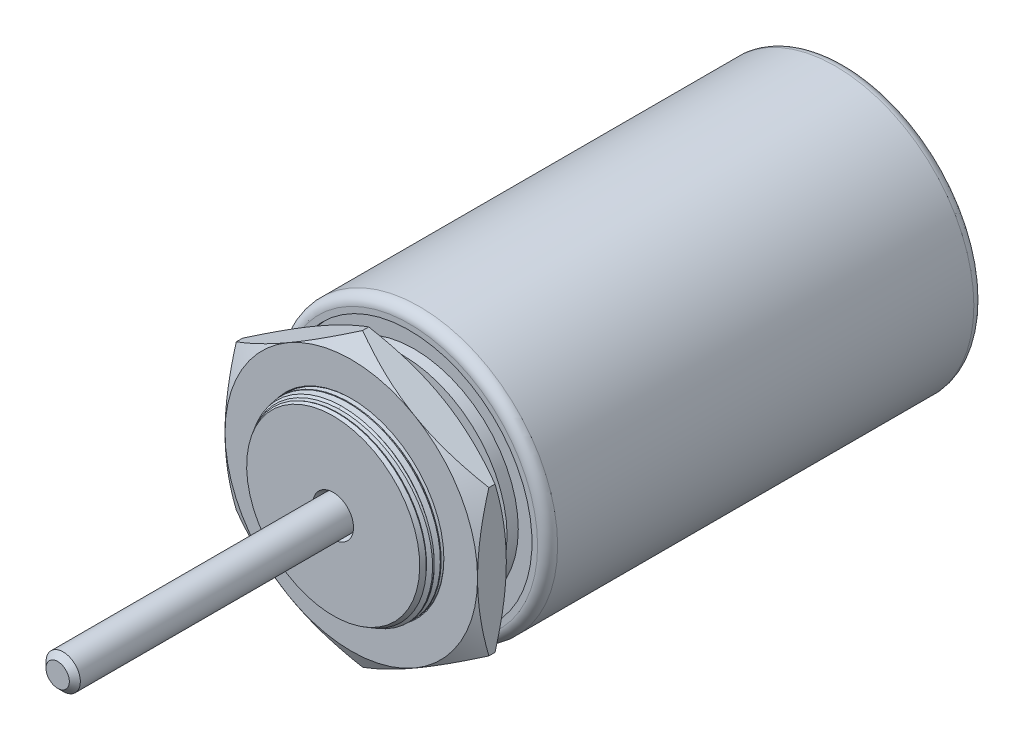
SolidWorks part; units mm, degrees
ref_plane "Front Plane" through (0, 0, 0) normal (0, 0, 1) x (1, 0, 0)
ref_plane "Top Plane" through (0, 0, 0) normal (0, 1, 0) x (1, 0, 0)
ref_plane "Right Plane" through (0, 0, 0) normal (1, 0, 0) x (0, 0, -1)
sketch "Sketch0" plane through (0, 0, 0) normal (1, 0, 0) x (0, 0, -1)
  line L0 (0, 0) -> (61.214, 0) construction
  line L1 (0, 0) -> (-26.3144, 0) construction
  line L2 (61.214, 19.1135) -> (61.214, -19.1135) construction
  line L3 (0, 12.7) -> (0, -12.7) construction
  line L4 (-26.3144, 2.3749) -> (-26.3144, -2.3749) construction
  line L5 (-26.3144, 0) -> (-51.7144, 0) construction
  line L6 (61.214, 0) -> (86.614, 0) construction
  line L7 (86.614, 0) -> (91.6432, 0) construction
  line L8 (88.4682, 6.35) -> (88.4682, -6.35) construction
  line L9 (91.6432, 2.8575) -> (91.6432, -2.8575) construction
  point P12 (-9.652, 0)
  point P17 (88.4682, 0)
  dimension "D1" = 5.715
  dimension "Lg." = 61.214
  dimension "Dia." = 38.227
  dimension "Rod Dia." = 4.7498
  dimension "A" = 42.0624
  dimension "Thread OD" = 25.4
  dimension "Stroke" = 25.4
  dimension "D2" = 3.175
  dimension "D3" = 9.652
  dimension "D4" = 5.0292
  dimension "End Dia." = 12.7
  dimension "D5" = 26.3144
sketch "Sketch1" plane through (0, 0, 0) normal (1, 0, 0) x (0, 0, -1)
  line L0 (61.214, 0) -> (0, 0) construction
  line L1 (59.8297, 19.1135) -> (2.2733, 19.1135)
  line L2 (0, 6.35) -> (61.214, 6.35)
  line L4 (1.5494, 16.9507) -> (1.5494, 14.3967)
  line L5 (61.214, 6.35) -> (61.214, 17.7292)
  line L6 (0.889, 17.7292) -> (0.889, 16.9507)
  line L7 (0.889, 16.9507) -> (1.5494, 16.9507)
  line L8 (1.5494, 14.3967) -> (0, 14.3967)
  line L9 (0, 14.3967) -> (0, 6.35)
  arc A1 (61.214, 17.7292) -> (59.8297, 19.1135) centre (59.8297, 17.7292) ccw
  arc A2 (0.889, 17.7292) -> (2.2733, 19.1135) centre (2.2733, 17.7292) cw
  dimension "D1" = 1.3843
  dimension "D4" = 0.889
  dimension "D5" = 33.9014
  dimension "D6" = 0.6604
  dimension "D7" = 28.7934
revolve "Revolve1" add sketch "Sketch1" angle 360 mid plane about L0
sketch "Sketch2" plane through (0, 0, 0) normal (1, 0, 0) x (0, 0, -1)
  line L0 (0, 0) -> (-26.3144, 0) construction
  line L3 (-9.652, 2.8148) -> (-9.652, 11.9668)
  line L4 (-9.652, 11.9668) -> (-8.382, 12.7)
  line L5 (-8.382, 12.7) -> (-3.2639, 12.7)
  line L6 (-3.2639, 12.7) -> (-1.5494, 10.9855)
  line L7 (-1.5494, 10.9855) -> (0, 10.9855)
  line L8 (0, 10.9855) -> (0, 2.3749)
  line L9 (-8.89, 2.3749) -> (0, 2.3749)
  line L11 (-8.89, 2.3749) -> (-9.652, 2.8148)
  dimension "D1" = 1.5494
  dimension "D2" = 45
  dimension "D3" = 30
  dimension "D4" = 1.27
  dimension "D5" = 9.652
  dimension "D6" = 1.7145
  dimension "D7" = 30
  dimension "D8" = 0.762
revolve "Revolve2" add sketch "Sketch2" angle 360 mid plane about L0
sketch "Sketch3" plane through (0, 0, 0) normal (1, 0, 0) x (0, 0, -1)
  line L0 (-9.652, 11.9668) -> (-9.652, -11.9668) construction
  line L1 (-46.99, 2.3749) -> (-47.752, 1.6129)
  line L2 (70.2056, 0) -> (-47.752, 0)
  line L3 (3.9624, 2.3749) -> (-46.99, 2.3749)
  line L4 (-47.752, 0) -> (-47.752, 1.6129)
  line L5 (-46.99, 2.3749) -> (-47.752, 2.3749) construction
  line L6 (-47.752, 2.3749) -> (-47.752, 1.6129) construction
  line L7 (3.9624, 6.35) -> (67.0306, 6.35)
  line L8 (67.0306, 6.35) -> (67.0306, 2.8575)
  line L9 (70.2056, 2.8575) -> (70.2056, 0)
  line L10 (67.0306, 2.8575) -> (70.2056, 2.8575)
  line L11 (3.9624, 6.35) -> (3.9624, 2.3749)
  point P1 (-59.6085, 69.5077)
  point P2 (-49.0748, 67.6511)
  point P3 (-63.5711, 53.1469)
  point P4 (-26.3144, 0)
  point P5 (-26.3144, 0)
  point P12 (-26.3144, 0)
  point P18 (0, 0)
  dimension "D1" = 0.762
  dimension "D2" = 2.3749
  dimension "D3" = 117.9576
  dimension "D4" = 63.0682
  dimension "D5" = 50.9524
  dimension "D6" = 3.9751
  dimension "D7" = 3.4925
  dimension "D8" = 38.1
revolve "Revolve3" add sketch "Sketch3" angle 360 mid plane about L2
sketch "Sketch6" plane through (0, 0, 9.652) normal (0, 0, 1) x (1, 0, 0)
  circle A1 centre (0, 0) radius 12.7
  point P1 (0, 12.7)
curve "Helix/Spiral1" pitch 0.9407 height 9.0433 turns 9.613 parameters "Pitch"=0.9407
sketch "Sketch7" plane through (0, 0, 0) normal (1, 0, 0) x (0, 0, -1)
  line L0 (-10.5339, 12.8018) -> (-9.5932, 12.8018) construction
  line L1 (-9.5932, 12.8018) -> (-10.0636, 11.9871) construction
  line L2 (-10.0636, 11.9871) -> (-10.5339, 12.8018) construction
  line L3 (-10.1224, 12.089) -> (-10.0048, 12.089) construction
  line L4 (-10.4751, 12.7) -> (-9.652, 12.7) construction
  line L5 (-10.0636, 11.9871) -> (-10.0636, 12.089) construction
  line L6 (-10.0636, 12.7) -> (-10.0636, 12.8018) construction
  line L7 (-10.1224, 12.089) -> (-10.0048, 12.089)
  line L8 (-10.0048, 12.089) -> (-9.6226, 12.7509)
  line L9 (-9.6226, 12.7509) -> (-10.5045, 12.7509)
  line L10 (-10.5045, 12.7509) -> (-10.1224, 12.089)
  line L11 (-10.0636, 11.9871) -> (-10.0636, -12.7) construction
  line L12 (-10.0636, -12.7) -> (-9.1228, -12.7) construction
  line L13 (-9.1228, -12.7) -> (-8.1821, -12.7) construction
  line L14 (-8.1821, -12.7) -> (-7.2414, -12.7) construction
  line L15 (-8.382, -12.7) -> (-3.2639, -12.7) construction
  point P15 (-10.0636, 12.7509)
  dimension "D1" = 0.9407
  dimension "D2" = 0.1176
sweep "Cut-Sweep1" cut profiles "Sketch7" path "Helix/Spiral1"
move or copy body "Body-Move/Copy1" [suppressed] bodies to move or copy 105 copy yes number of copies 1 translate (0, 0, 25.4)
sketch "SketchX" [suppressed] plane through (0, 0, 0) normal (1, 0, 0) x (0, 0, -1)
  line L3 (-51.7144, 1.6129) -> (-51.7144, -1.6129) construction
  line L4 (-51.7144, 1.6129) -> (-51.7144, -1.6129)
  line L6 (-50.9524, 2.3749) -> (-51.7144, 1.6129) construction
  line L9 (0, 2.3749) -> (-50.9524, 2.3749) construction
  line L10 (-51.7144, -1.6129) -> (-50.9524, -2.3749) construction
  line L13 (-50.9524, -2.3749) -> (0, -2.3749) construction
  line L14 (-50.9524, 2.3749) -> (-51.7144, 1.6129)
  line L15 (-25.5524, 2.3749) -> (-50.9524, 2.3749)
  line L16 (-51.7144, -1.6129) -> (-50.9524, -2.3749)
  line L17 (-50.9524, -2.3749) -> (-25.5524, -2.3749)
  line L18 (63.0682, 6.35) -> (0, 6.35) construction
  line L19 (63.0682, -6.35) -> (63.0682, 6.35) construction
  line L20 (66.2432, 2.8575) -> (63.0682, 2.8575) construction
  line L21 (66.2432, -2.8575) -> (66.2432, 2.8575) construction
  line L22 (0, -6.35) -> (63.0682, -6.35) construction
  line L23 (63.0682, 6.35) -> (61.214, 6.35)
  line L24 (63.0682, -6.35) -> (63.0682, -2.8575)
  line L25 (66.2432, 2.8575) -> (63.0682, 2.8575)
  line L26 (66.2432, -2.8575) -> (66.2432, 2.8575)
  line L27 (61.214, -6.35) -> (63.0682, -6.35)
  line L28 (61.214, -17.7292) -> (61.214, 17.7292) construction
  line L29 (63.0682, -2.8575) -> (66.2432, -2.8575) construction
  line L30 (63.0682, -2.8575) -> (66.2432, -2.8575)
  line L31 (63.0682, 2.8575) -> (63.0682, 6.35)
delete or keep bodies "Body-Delete1" [suppressed] type delete bodies bodies 108
sketch "Sketch8" plane through (0, 0, -61.214) normal (0, 0, -1) x (-1, 0, 0)
  line L0 (-15.9512, -2.54) -> (-15.9512, 2.54) construction
  line L1 (0, 0) -> (-15.9512, 0) construction
  circle A0 centre (-15.9512, 2.54) radius 0.254
  circle A1 centre (-15.9512, -2.54) radius 0.254
  dimension "D1" = 0.508
  dimension "D2" = 5.08
  dimension "D3" = 15.9512
extrude "Boss-Extrude1" [suppressed] add sketch "Sketch8" along normal blind 165.1
sketch "Sketch9" plane through (0, 0, -61.214) normal (0, 0, -1) x (-1, 0, 0)
  circle A0 centre (-15.9512, 2.54) radius 0.762
  circle A1 centre (-15.9512, -2.54) radius 0.762
  circle A3 centre (-15.9512, -2.54) radius 0.254
  circle A4 centre (-15.9512, -2.54) radius 0.254
  circle A5 centre (-15.9512, 2.54) radius 0.254
  circle A6 centre (-15.9512, 2.54) radius 0.254
  dimension "D3" = 1.524
  dimension "D1" = 0
  dimension "D2" = 0
extrude "Boss-Extrude2" [suppressed] add sketch "Sketch9" along normal blind 152.4
sketch "Sketch10" plane through (0, 0, 0) normal (0, 0, 1) x (1, 0, 0)
  line L0 (0, 12.7) -> (0, 17.4625) construction
  line L1 (0, 20.164) -> (-17.4625, 10.082)
  line L2 (-17.4625, 10.082) -> (-17.4625, -10.082)
  line L3 (-17.4625, -10.082) -> (0, -20.164)
  line L4 (0, -20.164) -> (17.4625, -10.082)
  line L5 (17.4625, -10.082) -> (17.4625, 10.082)
  line L6 (17.4625, 10.082) -> (0, 20.164)
  circle A0 centre (0, 0) radius 12.7
  circle A1 centre (0, 0) radius 17.4625 construction
  dimension "D1" = 34.925
extrude "Boss-Extrude3" add sketch "Sketch10" along normal blind 3.9688 from offset 3.175 separate body
sketch "Sketch11" plane through (0, 0, 0) normal (1, 0, 0) x (0, 0, -1)
  line L0 (-7.1438, 0) -> (-3.175, 0) construction
  line L2 (-7.1437, 12.7) -> (-7.1437, -12.7) construction
  line L3 (-3.175, -12.7) -> (-3.175, 12.7) construction
  line L4 (-7.1437, 20.164) -> (-7.1437, 17.4625)
  line L5 (-7.1437, 10.082) -> (-7.1437, 20.164) construction
  line L6 (-7.1437, 17.4625) -> (-5.5841, 20.164)
  line L7 (-7.1437, 20.164) -> (-3.175, 20.164) construction
  line L8 (-5.5841, 20.164) -> (-7.1437, 20.164)
  line L9 (-3.175, 20.164) -> (-3.175, 17.4625)
  line L10 (-3.175, 10.082) -> (-3.175, 20.164) construction
  line L11 (-3.175, 17.4625) -> (-4.7347, 20.164)
  line L12 (-4.7347, 20.164) -> (-3.175, 20.164)
  line L13 (-7.1437, 17.4625) -> (0, 17.4625) construction
  line L14 (-7.1437, 12.8018) -> (-7.1437, 12.7)
  line L15 (-7.1437, 12.7) -> (-7.0419, 12.7)
  line L16 (-7.0419, 12.7) -> (-7.1437, 12.8018)
  line L17 (-3.175, 12.8018) -> (-3.175, 12.7)
  line L18 (-3.175, 12.7) -> (-3.2768, 12.7)
  line L19 (-3.2768, 12.7) -> (-3.175, 12.8018)
  line L20 (-7.1437, 12.8018) -> (-10.0636, 12.8018) construction
  dimension "D1" = 30
revolve "Cut-Revolve1" cut sketch "Sketch11" angle 360 about L0
equation "\"D3@Helix/Spiral1\" = \"Pitch@Helix/Spiral1\" + \"D5@Sketch2\" - \"D1@Sketch2\""
equation "\"D1@Sketch7\" = \"Pitch@Helix/Spiral1\""
equation "\"D2@Sketch7\" = \"D1@Sketch7\" / 8"
